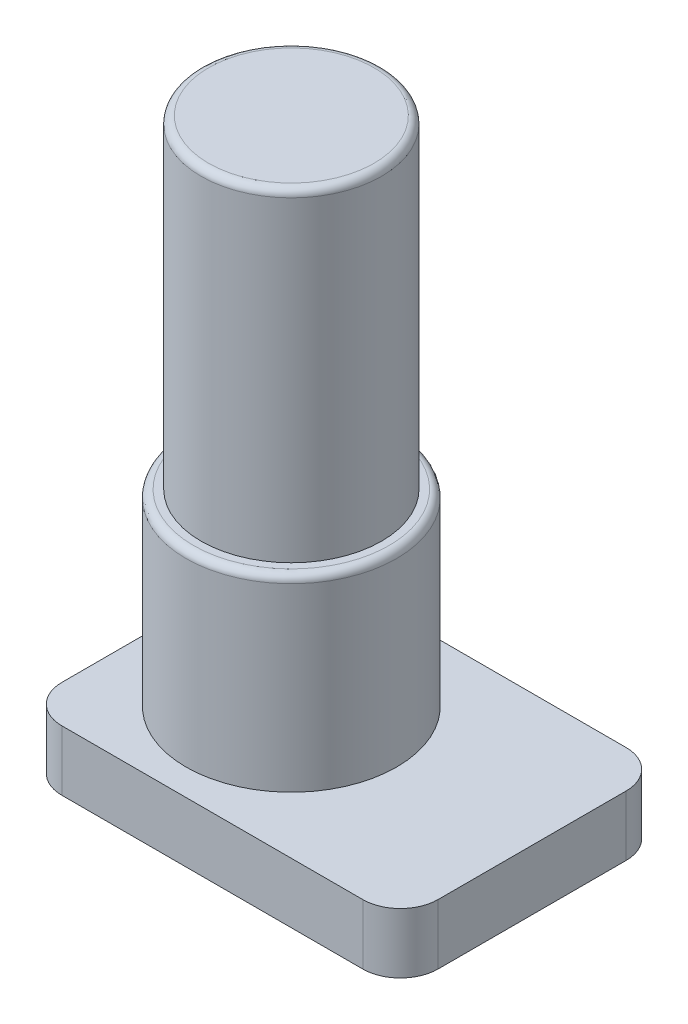
SolidWorks part; units mm, degrees
ref_plane "Front Plane" through (0, 0, 0) normal (0, 0, 1) x (1, 0, 0)
ref_plane "Top Plane" through (0, 0, 0) normal (0, 1, 0) x (1, 0, 0)
ref_plane "Right Plane" through (0, 0, 0) normal (1, 0, 0) x (0, 0, -1)
sketch "Sketch1" plane through (0, 0, 0) normal (0, 1, 0) x (1, 0, 0)
  line L1 (-25, 17.5) -> (25, 17.5)
  line L2 (-25, 17.5) -> (-25, -17.5)
  line L3 (-25, -17.5) -> (25, -17.5)
  line L4 (25, 17.5) -> (25, -17.5)
  line L5 (-25, 17.5) -> (25, -17.5) construction
  line L6 (-25, -17.5) -> (25, 17.5) construction
  point P0 (0, 0)
  dimension "D1" = 50
  dimension "D2" = 35
extrude "Boss-Extrude1" add sketch "Sketch1" along normal blind 8
sketch "Sketch2" plane through (0, 8, 0) normal (0, 1, 0) x (1, 0, 0)
  line L0 (-7, 17.5) -> (-7, -17.5) construction
  line L1 (25, 17.5) -> (-25, 17.5) construction
  line L2 (-25, -17.5) -> (25, -17.5) construction
  line L3 (-25, 17.5) -> (-25, -17.5) construction
  circle A0 centre (-7, 0) radius 14
  dimension "D1" = 28
  dimension "D2" = 18
extrude "Boss-Extrude2" add sketch "Sketch2" along normal blind 25
sketch "Sketch3" plane through (0, 33, 0) normal (0, 1, 0) x (1, 0, 0)
  circle A0 centre (-7, 0) radius 12
  dimension "D1" = 24
extrude "Boss-Extrude3" add sketch "Sketch3" along normal blind 43
fillet "Fillet1" radius 5 4 edges at (-25, 4, -17.5) (-25, 4, 17.5) (25, 4, -17.5) (25, 4, 17.5)
fillet "Fillet2" radius 1 2 edges at (-7, 76, 12) (-7, 33, 14)
